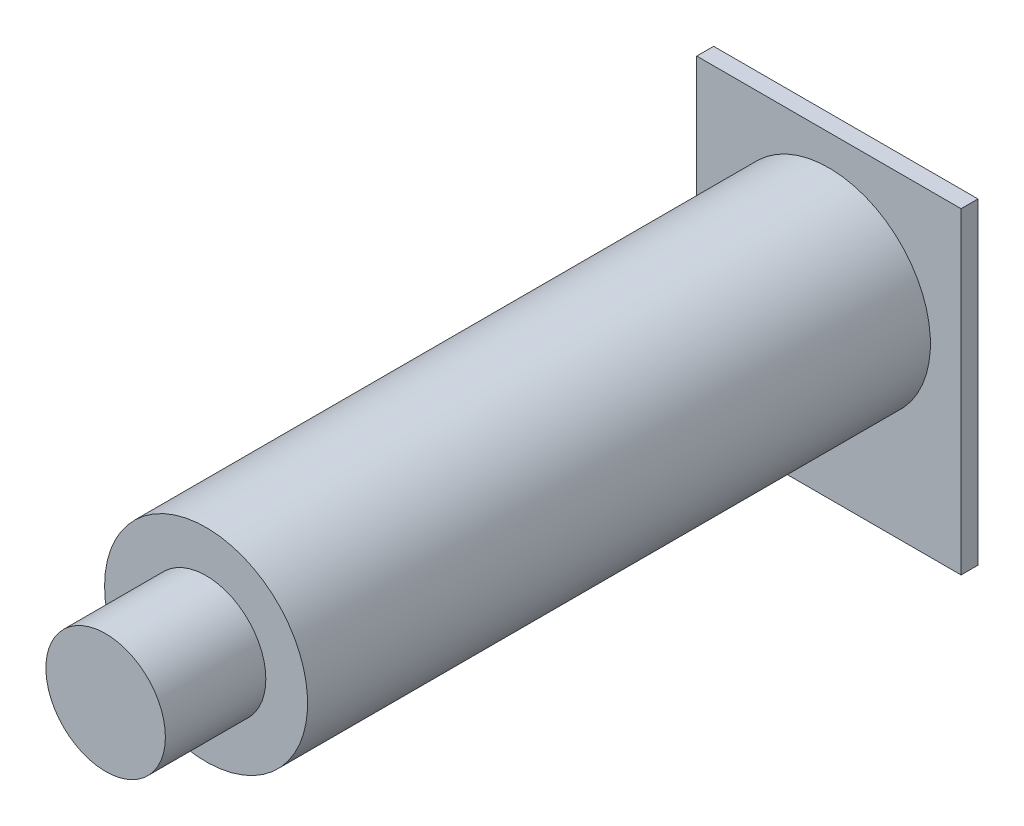
SolidWorks part; units mm, degrees
ref_plane "正面" through (0, 0, 0) normal (0, 0, 1) x (1, 0, 0)
ref_plane "平面" through (0, 0, 0) normal (0, 1, 0) x (1, 0, 0)
ref_plane "右側面" through (0, 0, 0) normal (1, 0, 0) x (0, 0, -1)
sketch "ｽｹｯﾁ1" plane through (0, 0, 0) normal (0, 0, 1) x (1, 0, 0)
  line L1 (-27.2658, 34.3643) -> (-2.2658, 34.3643)
  line L2 (-27.2658, 34.3643) -> (-27.2658, 4.3643)
  line L3 (-27.2658, 4.3643) -> (-2.2658, 4.3643)
  line L4 (-2.2658, 34.3643) -> (-2.2658, 4.3643)
  dimension "D3" = 25
  dimension "D4" = 30
extrude "ﾎﾞｽ - 押し出し1" add sketch "ｽｹｯﾁ1" along normal blind 1.6
sketch "ｽｹｯﾁ2" plane through (0, 0, 1.6) normal (0, 0, 1) x (1, 0, 0)
  line L1 (-2.2658, 4.3643) -> (-2.2658, 34.3643) construction
  line L2 (-2.2658, 34.3643) -> (-27.2658, 34.3643) construction
  circle A0 centre (-14.7658, 21.8643) radius 9.6
  point P6 (0, 0)
  dimension "D1" = 19.2
  dimension "D2" = 12.5
  dimension "D3" = 12.5
extrude "ﾎﾞｽ - 押し出し2" add sketch "ｽｹｯﾁ2" along normal blind 58.9
sketch "ｽｹｯﾁ4" plane through (0, 0, 60.5) normal (0, 0, 1) x (1, 0, 0)
  circle A0 centre (-14.7658, 21.8643) radius 5.65
  circle A1 centre (-14.7658, 21.8643) radius 9.6 construction
  dimension "D1" = 11.3
extrude "ﾎﾞｽ - 押し出し3" add sketch "ｽｹｯﾁ4" along normal blind 9.5
